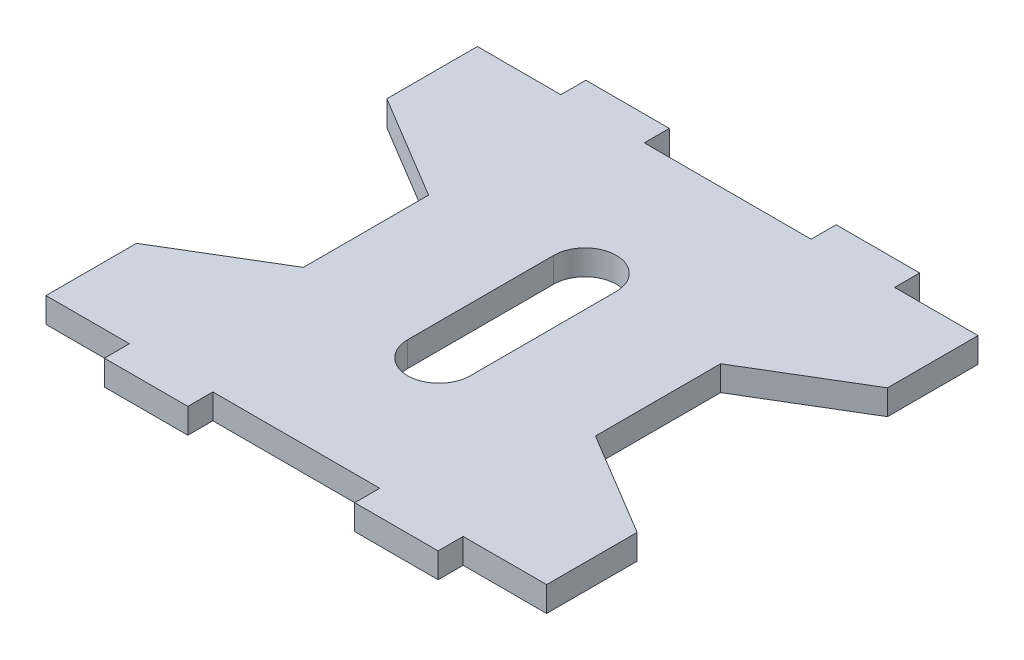
SolidWorks part; units mm, degrees
ref_plane "前视基准面" through (0, 0, 0) normal (0, 0, 1) x (1, 0, 0)
ref_plane "上视基准面" through (0, 0, 0) normal (0, 1, 0) x (1, 0, 0)
ref_plane "右视基准面" through (0, 0, 0) normal (1, 0, 0) x (0, 0, -1)
sketch "草图2" plane through (0, 0, 0) normal (0, 1, 0) x (1, 0, 0)
  line L0 (-11.1667, 0) -> (11.1667, 0) construction
  line L1 (0, 45.0766) -> (0, -45.0766) construction
  line L2 (-10, 25.85) -> (10, 25.85)
  line L3 (10, 25.85) -> (10, 28.85)
  line L4 (10, 28.85) -> (20, 28.85)
  line L5 (20, 28.85) -> (20, 25.85)
  line L6 (20, 25.85) -> (30, 25.85)
  line L7 (30, 25.85) -> (30, 15)
  line L8 (30, 15) -> (17.5, 7.5)
  line L9 (17.5, 7.5) -> (17.5, -7.5)
  line L10 (-17.5, 7.5) -> (-17.5, -7.5)
  line L11 (-30, 15) -> (-17.5, 7.5)
  line L12 (-30, 25.85) -> (-30, 15)
  line L13 (-20, 25.85) -> (-30, 25.85)
  line L14 (-20, 28.85) -> (-20, 25.85)
  line L15 (-10, 28.85) -> (-20, 28.85)
  line L16 (-10, 25.85) -> (-10, 28.85)
  line L17 (-10, -25.85) -> (-10, -28.85)
  line L18 (-10, -28.85) -> (-20, -28.85)
  line L19 (-20, -28.85) -> (-20, -25.85)
  line L20 (-20, -25.85) -> (-30, -25.85)
  line L21 (-30, -25.85) -> (-30, -15)
  line L22 (-30, -15) -> (-17.5, -7.5)
  line L23 (30, -15) -> (17.5, -7.5)
  line L24 (30, -25.85) -> (30, -15)
  line L25 (20, -25.85) -> (30, -25.85)
  line L26 (20, -28.85) -> (20, -25.85)
  line L27 (10, -28.85) -> (20, -28.85)
  line L28 (10, -25.85) -> (10, -28.85)
  line L29 (-10, -25.85) -> (10, -25.85)
  line L30 (3.75, -8.75) -> (3.75, 8.75)
  line L31 (-3.75, -8.75) -> (-3.75, 8.75)
  arc A0 (3.75, 8.75) -> (-3.75, 8.75) centre (0, 8.75) ccw
  arc A1 (3.75, -8.75) -> (-3.75, -8.75) centre (0, -8.75) cw
  point P0 (0, -25.85)
  point P4 (0, 0)
  point P8 (0, 0)
  point P25 (0, 25.85)
  point P33 (-17.5, 0)
  point P34 (17.5, 0)
  point P45 (3.75, 0)
  point P46 (-3.75, 0)
  dimension "D10" = 7.5
  dimension "D11" = 3.75
  dimension "D1" = 51.7
  dimension "D2" = 60
  dimension "D3" = 3
  dimension "D4" = 10
  dimension "D5" = 10
  dimension "D6" = 10.85
  dimension "D7" = 12.5
  dimension "D8" = 7.5
  dimension "D9" = 8.75
extrude "凸台-拉伸1" add sketch "草图2" along normal blind 3
